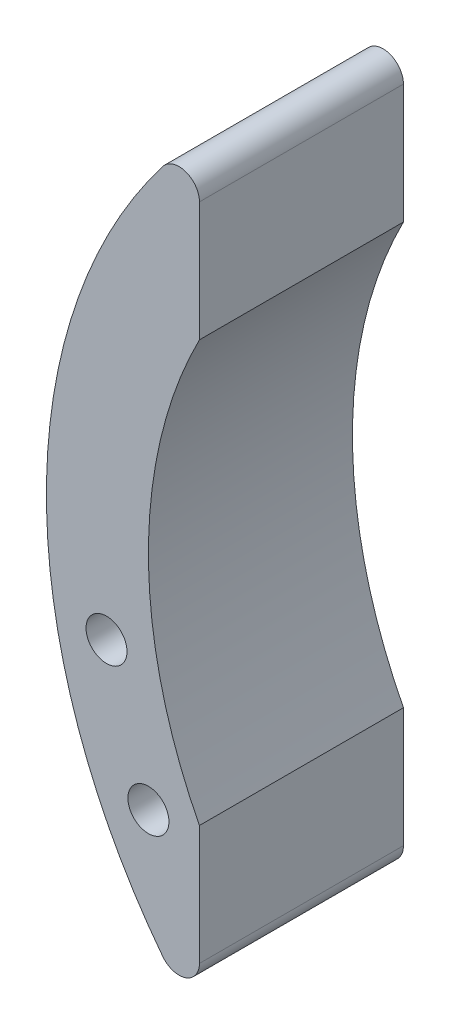
SolidWorks part; units mm, degrees
ref_plane "Front Plane" through (0, 0, 0) normal (0, 0, 1) x (1, 0, 0)
ref_plane "Top Plane" through (0, 0, 0) normal (0, 1, 0) x (1, 0, 0)
ref_plane "Right Plane" through (0, 0, 0) normal (1, 0, 0) x (0, 0, -1)
sketch "Sketch1" plane through (0, 0, 0) normal (0, 0, 1) x (1, 0, 0)
  line L0 (69.85, 0) -> (57.15, 0) construction
  line L1 (-69.85, 0) -> (69.85, 0) construction
  dimension "OD" = 139.7
  dimension "Wall Thickness" = 12.7
sketch "Sketch2" plane through (0, 0, 0) normal (1, 0, 0) x (0, 0, -1)
  line L0 (12.7, 0) -> (-12.7, 0)
  point P4 (0, 0)
  dimension "Length" = 25.4
sketch "Sketch3" plane through (0, 0, 0) normal (0, 0, 1) x (1, 0, 0)
  circle A0 centre (0, 0) radius 69.85
  circle A1 centre (0, 0) radius 57.15
extrude "Boss-Extrude1" add sketch "Sketch3" along normal up to vertex (12.7 mm away) and the other way up to vertex (12.7 mm away) up to point (0, 0, 12.7) other way up to point (0, 0, -12.7)
sketch "Sketch4" plane through (0, 0, 12.7) normal (0, 0, 1) x (1, 0, 0)
  line L0 (-50.8, 69.1203) -> (-50.8, -69.1203)
  line L1 (-44.45, -111.9186) -> (44.45, -111.9186) construction
  line L2 (-44.45, -111.9186) -> (-44.45, 111.9186) construction
  line L3 (-44.45, 111.9186) -> (44.45, 111.9186) construction
  line L4 (44.45, -111.9186) -> (44.45, 111.9186) construction
  line L5 (-44.45, -111.9186) -> (44.45, 111.9186) construction
  line L6 (-44.45, 111.9186) -> (44.45, -111.9186) construction
  line L9 (-50.8, 111.9186) -> (-50.8, -111.9186) construction
  circle A1 centre (0, 0) radius 85.7803 construction
  arc A2 (-50.8, -69.1203) -> (-50.8, 69.1203) centre (0, 0) ccw
  point P0 (0, 0)
  dimension "D2" = 171.5606
  dimension "D1" = 88.9
  dimension "D3" = 6.35
  dimension "D4" = 223.8371
extrude "Cut-Extrude1" cut sketch "Sketch4" against normal through all
sketch "Sketch5" plane through (0, 0, 12.7) normal (0, 0, 1) x (1, 0, 0)
  line L0 (0, 0) -> (-51.435, -24.9111) construction
  line L1 (-51.435, -24.9111) -> (-62.865, -30.4469) construction
  line L2 (0, 0) -> (-56.1299, -10.7499) construction
  line L3 (-56.1299, -10.7499) -> (-68.6032, -13.1388) construction
  line L4 (-44.45, -111.9186) -> (-44.45, 111.9186) construction
  arc A0 (-50.8, 26.1817) -> (-50.8, -26.1817) centre (0, 0) ccw construction
  arc A1 (-50.8, 47.9414) -> (-50.8, -47.9414) centre (0, 0) ccw construction
  point P0 (-57.15, -27.679)
  point P1 (-62.3665, -11.9444)
  dimension "D1" = 12.7
  dimension "D2" = 15
hole_wizard "Tap Drill for 1/4-20 Tap1" positions "Sketch5" profile "Sketch6" hole size "1/4-20" standard "ANSI Inch" end condition through all
sketch "Sketch6" plane through (-57.15, -27.679, 12.7) normal (1, 0, 0) x (0, -1, 0)
  line L0 (0, 0) -> (0, 25.4)
  line L1 (0, 25.4) -> (2.5527, 25.4)
  line L2 (2.5527, 25.4) -> (2.5527, 0)
  line L5 (2.5527, 0) -> (0, 0)
  line L11 (0, -6.35) -> (0, 107.95) construction
  dimension "Thru Hole Dia." = 5.1054
  dimension "Thru Hole Depth" = 25.4
fillet "Fillet1" radius 2.54 2 edges at (-50.8, 47.9414, 0) (-50.8, -47.9414, 0)
